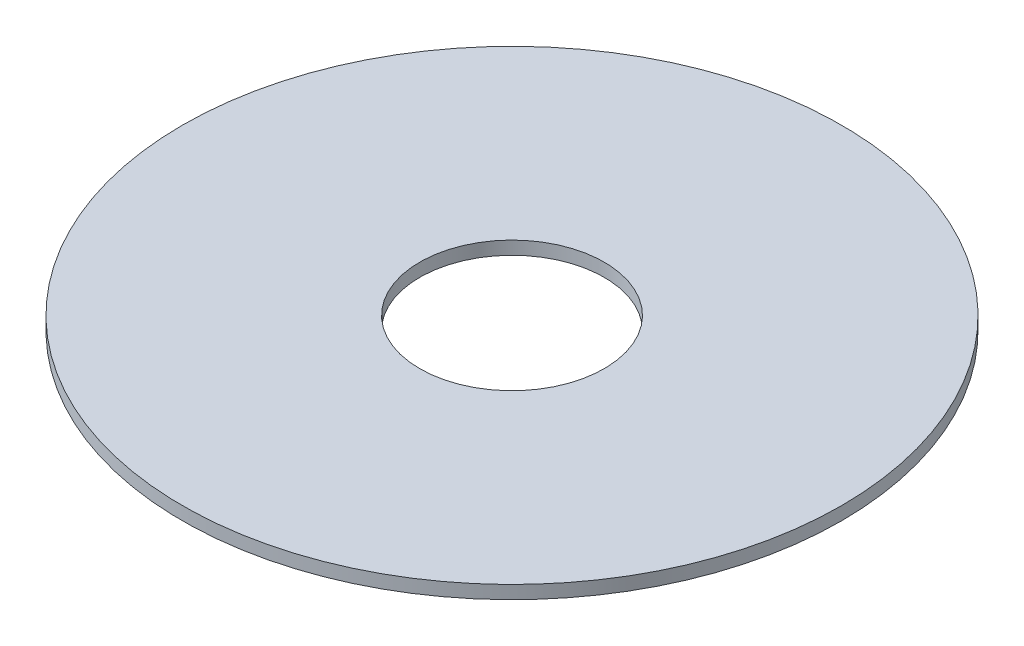
SolidWorks part; units mm, degrees
material "Plain Carbon Steel"
ref_plane "Front Plane" through (0, 0, 0) normal (0, 0, 1) x (1, 0, 0)
ref_plane "Top Plane" through (0, 0, 0) normal (0, 1, 0) x (1, 0, 0)
ref_plane "Right Plane" through (0, 0, 0) normal (1, 0, 0) x (0, 0, -1)
sketch "Sketch1" plane through (0, 0, 0) normal (0, 1, 0) x (1, 0, 0)
  circle A0 centre (0, 0) radius 7
  dimension "D1" = 14
extrude "Extrude-Thin1" add sketch "Sketch1" along normal blind 1 thin
